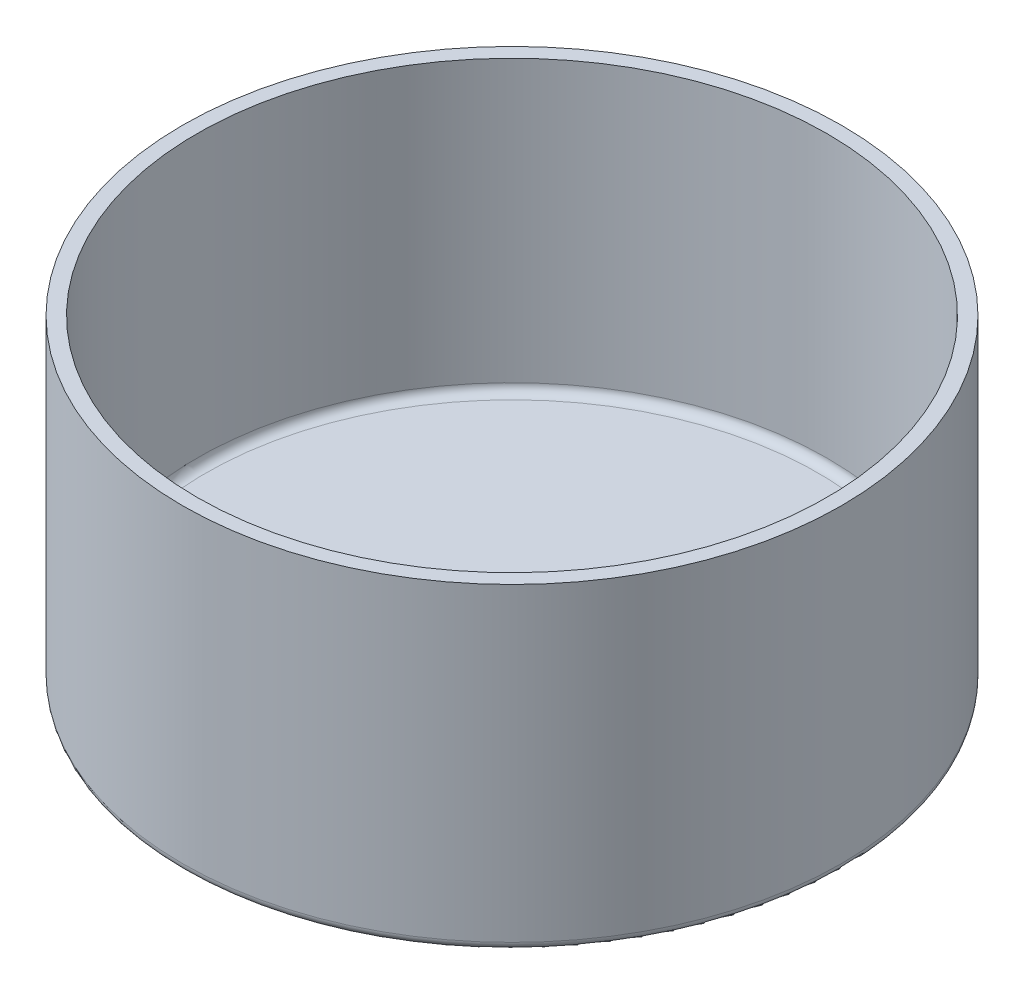
SolidWorks part; units mm, degrees
ref_plane "Alzado" through (0, 0, 0) normal (0, 0, 1) x (1, 0, 0)
ref_plane "Planta" through (0, 0, 0) normal (0, 1, 0) x (1, 0, 0)
ref_plane "Vista lateral" through (0, 0, 0) normal (1, 0, 0) x (0, 0, -1)
sketch "Croquis1" plane through (0, 0, 0) normal (0, 1, 0) x (1, 0, 0)
  circle A0 centre (0, 0) radius 11.375
  dimension "D1" = 22.75
extrude "Saliente-Extruir1" add sketch "Croquis1" along normal blind 1
sketch "Croquis2" plane through (0, 1, 0) normal (0, 1, 0) x (1, 0, 0)
  circle A0 centre (0, 0) radius 11.375
  circle A1 centre (0, 0) radius 10.875
  dimension "D1" = 22.75
  dimension "D2" = 21.75
extrude "Saliente-Extruir2" add sketch "Croquis2" along normal blind 10
fillet "Redondeo1" radius 0.3 1 edges at (0, 1, 10.875)
fillet "Redondeo2" radius 0.3 1 edges at (0, 0, 11.375)
